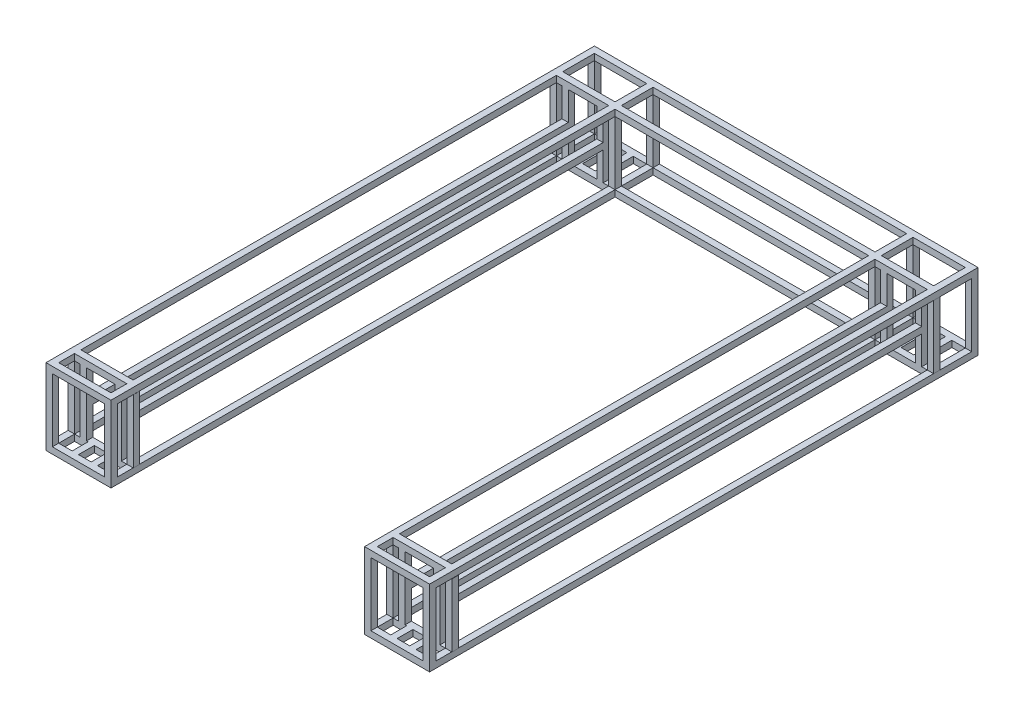
SolidWorks part; units mm, degrees
ref_plane "Front Plane" through (0, 0, 0) normal (0, 0, 1) x (1, 0, 0)
ref_plane "Top Plane" through (0, 0, 0) normal (0, 1, 0) x (1, 0, 0)
ref_plane "Right Plane" through (0, 0, 0) normal (1, 0, 0) x (0, 0, -1)
sketch "Sketch1" plane through (0, 0, 0) normal (0, 1, 0) x (1, 0, 0)
  line L0 (-400, 865) -> (-400, -865) construction
  line L1 (-400, 865) -> (400, 865) construction
  line L2 (-400, 865) -> (-400, -865) construction
  line L3 (-400, -865) -> (400, -865) construction
  line L4 (400, 865) -> (400, -865) construction
  line L5 (-400, 865) -> (400, -865) construction
  line L6 (-400, -865) -> (400, 865) construction
  line L7 (-400, 865) -> (-605, 865) construction
  line L8 (-400, -865) -> (-605, -865) construction
  line L9 (-605, 865) -> (-605, -865) construction
  line L10 (-605, 865) -> (-605, -865)
  line L11 (-605, 865) -> (-585, 865)
  line L12 (-605, -865) -> (-585, -865)
  line L13 (-585, 865) -> (-585, -865)
  line L14 (-400, 865) -> (-400, -865)
  line L15 (-400, 865) -> (-420, 865)
  line L16 (-400, -865) -> (-420, -865)
  line L17 (-420, 865) -> (-420, -865)
  line L18 (-420, -865) -> (-585, -865)
  line L21 (-420, -845) -> (-585, -845)
  line L22 (-585, -795) -> (-420, -795)
  line L25 (-585, -775) -> (-420, -775)
  line L26 (-585, 865) -> (-420, 865)
  line L29 (-585, 845) -> (-420, 845)
  line L30 (-420, 745) -> (-585, 745)
  line L33 (-420, 725) -> (-585, 725)
  line L34 (0, -55) -> (0, 55) construction
  line L35 (605, 865) -> (605, -865) construction
  line L36 (400, -865) -> (605, -865) construction
  line L37 (400, 865) -> (605, 865) construction
  line L38 (400, -865) -> (-400, 865) construction
  line L39 (400, 865) -> (-400, -865) construction
  line L40 (-400, 865) -> (-400, -865) construction
  line L41 (400, 865) -> (400, -865) construction
  line L42 (400, 865) -> (400, -865) construction
  line L43 (420, 725) -> (585, 725)
  line L46 (420, 745) -> (585, 745)
  line L47 (585, 845) -> (420, 845)
  line L50 (585, 865) -> (420, 865)
  line L51 (585, -775) -> (420, -775)
  line L54 (585, -795) -> (420, -795)
  line L55 (420, -845) -> (585, -845)
  line L58 (420, -865) -> (585, -865)
  line L59 (420, 865) -> (420, -865)
  line L60 (400, -865) -> (420, -865)
  line L61 (400, 865) -> (420, 865)
  line L62 (400, 865) -> (400, -865)
  line L63 (585, 865) -> (585, -865)
  line L64 (605, -865) -> (585, -865)
  line L65 (605, 865) -> (585, 865)
  line L66 (605, 865) -> (605, -865)
  line L67 (-400, 865) -> (400, 865)
  line L68 (400, 845) -> (-400, 845)
  line L69 (-400, 745) -> (400, 745)
  line L71 (400, 725) -> (-400, 725)
  point P0 (0, 0)
  dimension "D1" = 1730
  dimension "D2" = 800
  dimension "D3" = 165
  dimension "D4" = 20
  dimension "D5" = 20
  dimension "D6" = 20
  dimension "D7" = 20
  dimension "D8" = 100
  dimension "D9" = 20
  dimension "D10" = 20
  dimension "D11" = 50
extrude "Boss-Extrude1" add sketch "Sketch1" along normal blind 20 contours L13 L11 L10 L12 | L15 L17 L16 L14 | L33 L17 L30 L13 | L13 L29 L17 L26 | L71 L62 L69 L14 | L68 L62 L67 L14 | L63 L50 L59 L47 | L61 L62 L60 L59 | L63 L46 L59 L43 | L66 L65 L63 L64 | L63 L51 L59 L54 | L63 L55 L59 L58 | L25 L13 L22 L17 | L17 L21 L13 L18
pattern_linear "LPattern1" count 2 spacing 220 along (0, -1, 0) of "Boss-Extrude1"
sketch "Sketch2" plane through (0, 0, 0) normal (0, 1, 0) x (1, 0, 0)
  line L0 (-585, 745) -> (-585, 725)
  line L1 (-605, 865) -> (-585, 865)
  line L2 (-605, 865) -> (-605, 845)
  line L3 (-605, 845) -> (-585, 845)
  line L4 (-585, 865) -> (-585, 845)
  line L5 (-585, 745) -> (-605.1132, 745)
  line L6 (-585, 725) -> (-605.1132, 725)
  line L7 (-605.1132, 745) -> (-605.1132, 725)
  line L8 (-420, 845) -> (-400, 845)
  line L9 (-420, 845) -> (-420, 865.7864)
  line L10 (-400, 845) -> (-400, 865.7864)
  line L11 (-420, 865.7864) -> (-400, 865.7864)
  line L12 (-585, -795) -> (-585, -775)
  line L13 (-400, 745) -> (-420, 745)
  line L14 (-400, 745) -> (-400, 725)
  line L15 (-400, 725) -> (-420, 725)
  line L16 (-420, 745) -> (-420, 725)
  line L17 (-585, -845) -> (-605, -845)
  line L18 (-585, -845) -> (-585, -865)
  line L19 (-585, -865) -> (-605, -865)
  line L20 (-605, -845) -> (-605, -865)
  line L21 (-420, -845) -> (-400, -845)
  line L22 (-420, -845) -> (-420, -865)
  line L23 (-420, -865) -> (-400, -865)
  line L24 (-400, -845) -> (-400, -865)
  line L25 (-585, -795) -> (-605.9457, -795)
  line L26 (-585, -775) -> (-605.9457, -775)
  line L27 (-605.9457, -795) -> (-605.9457, -775)
  line L28 (-420, -775) -> (-420, -795)
  line L29 (-420, -775) -> (-399.5604, -775)
  line L30 (-420, -795) -> (-399.5604, -795)
  line L31 (-399.5604, -775) -> (-399.5604, -795)
  line L32 (0, -55) -> (0, 55) construction
  line L33 (605.9457, -795) -> (605.9457, -775)
  line L34 (585, -775) -> (605.9457, -775)
  line L35 (585, -795) -> (605.9457, -795)
  line L36 (400, -845) -> (400, -865)
  line L37 (420, -865) -> (400, -865)
  line L38 (420, -845) -> (420, -865)
  line L39 (420, -845) -> (400, -845)
  line L40 (605, -845) -> (605, -865)
  line L41 (585, -865) -> (605, -865)
  line L42 (585, -845) -> (585, -865)
  line L43 (585, -845) -> (605, -845)
  line L44 (420, 745) -> (420, 725)
  line L45 (400, 725) -> (420, 725)
  line L46 (400, 745) -> (400, 725)
  line L47 (400, 745) -> (420, 745)
  line L48 (585, -795) -> (585, -775)
  line L49 (420, 865.7864) -> (400, 865.7864)
  line L50 (400, 845) -> (400, 865.7864)
  line L51 (420, 845) -> (420, 865.7864)
  line L52 (420, 845) -> (400, 845)
  line L53 (605.1132, 745) -> (605.1132, 725)
  line L54 (585, 725) -> (605.1132, 725)
  line L55 (585, 745) -> (605.1132, 745)
  line L56 (585, 865) -> (585, 845)
  line L57 (605, 845) -> (585, 845)
  line L58 (605, 865) -> (605, 845)
  line L59 (605, 865) -> (585, 865)
  line L60 (585, 745) -> (585, 725)
  line L61 (420, -795) -> (399.5604, -795)
  line L62 (399.5604, -775) -> (399.5604, -795)
  line L63 (420, -775) -> (399.5604, -775)
  line L64 (420, -775) -> (420, -795)
extrude "Boss-Extrude2" add sketch "Sketch2" against normal blind 200
sketch "Sketch3" plane through (0, -220, 0) normal (0, -1, 0) x (1, 0, 0)
  line L0 (-502.5, -845) -> (-502.5, 865) construction
  line L1 (-585, -845) -> (-420, -845) construction
  line L2 (-420, -745) -> (-585, -745) construction
  line L3 (-482.5, -745) -> (-462.5, -745)
  line L4 (-482.5, -745) -> (-482.5, -845)
  line L5 (-482.5, -845) -> (-462.5, -845)
  line L6 (-462.5, -745) -> (-462.5, -845)
  line L7 (-605, 865) -> (-400, 865) construction
  line L8 (-542.5, -745) -> (-522.5, -745)
  line L9 (-542.5, -745) -> (-542.5, -845)
  line L10 (-542.5, -845) -> (-522.5, -845)
  line L11 (-522.5, -745) -> (-522.5, -845)
  line L12 (-420, 845) -> (-585, 845) construction
  line L13 (-462.5, 845) -> (-482.5, 845)
  line L14 (-462.5, 845) -> (-462.5, 795)
  line L15 (-462.5, 795) -> (-482.5, 795)
  line L16 (-482.5, 845) -> (-482.5, 795)
  line L17 (-585, 795) -> (-420, 795) construction
  line L18 (0, -55) -> (0, 55) construction
  line L19 (-542.5, 845) -> (-522.5, 845)
  line L20 (-542.5, 845) -> (-542.5, 795)
  line L21 (-542.5, 795) -> (-522.5, 795)
  line L22 (-522.5, 845) -> (-522.5, 795)
  line L23 (522.5, 845) -> (522.5, 795)
  line L24 (542.5, 795) -> (522.5, 795)
  line L25 (542.5, 845) -> (542.5, 795)
  line L26 (542.5, 845) -> (522.5, 845)
  line L27 (482.5, 845) -> (482.5, 795)
  line L28 (462.5, 795) -> (482.5, 795)
  line L29 (462.5, 845) -> (462.5, 795)
  line L30 (462.5, 845) -> (482.5, 845)
  line L31 (522.5, -745) -> (522.5, -845)
  line L32 (542.5, -845) -> (522.5, -845)
  line L33 (542.5, -745) -> (542.5, -845)
  line L34 (542.5, -745) -> (522.5, -745)
  line L35 (462.5, -745) -> (462.5, -845)
  line L36 (482.5, -845) -> (462.5, -845)
  line L37 (482.5, -745) -> (482.5, -845)
  line L38 (482.5, -745) -> (462.5, -745)
  dimension "D1" = 20
  dimension "D2" = 20
  dimension "D3" = 20
  dimension "D4" = 20
  dimension "D5" = 20
  dimension "D6" = 20
  dimension "D7" = 20
  dimension "D8" = 20
extrude "Boss-Extrude3" add sketch "Sketch3" against normal blind 20
sketch "Sketch4" plane through (0, 0, -725) normal (0, 0, 1) x (1, 0, 0)
  line L0 (-502.5, 0) -> (-502.5, -200) construction
  line L1 (-585, 0) -> (-420, 0) construction
  line L2 (-585, -200) -> (-420, -200) construction
  line L3 (0, -55) -> (0, 55) construction
  line L4 (-437.5, 0) -> (-457.5, 0)
  line L5 (-437.5, 0) -> (-437.5, -200)
  line L6 (-437.5, -200) -> (-457.5, -200)
  line L7 (-457.5, 0) -> (-457.5, -200)
  line L8 (-547.5, 0) -> (-567.5, 0)
  line L9 (-547.5, 0) -> (-547.5, -200)
  line L10 (-547.5, -200) -> (-567.5, -200)
  line L11 (-567.5, 0) -> (-567.5, -200)
  line L12 (502.5, 0) -> (502.5, -200) construction
  line L13 (567.5, 0) -> (567.5, -200)
  line L14 (547.5, -200) -> (567.5, -200)
  line L15 (547.5, 0) -> (547.5, -200)
  line L16 (547.5, 0) -> (567.5, 0)
  line L17 (457.5, 0) -> (457.5, -200)
  line L18 (437.5, -200) -> (457.5, -200)
  line L19 (437.5, 0) -> (437.5, -200)
  line L20 (437.5, 0) -> (457.5, 0)
  dimension "D1" = 20
  dimension "D2" = 20
  dimension "D3" = 45
  dimension "D4" = 45
extrude "Boss-Extrude4" add sketch "Sketch4" against normal blind 20
pattern_linear "LPattern2" count 2 spacing 1520 along (0, 0, 1) of "Boss-Extrude4"
sketch "Sketch5" plane through (0, 0, -725) normal (0, 0, 1) x (1, 0, 0)
  line L0 (-547.5, -200) -> (-547.5, 0) construction
  line L5 (-547.5, 0) -> (-567.5, -200) construction
  line L6 (-567.5, 0) -> (-547.5, -200) construction
  line L7 (-585, -200) -> (-420, -200) construction
  line L8 (-502.5, 0) -> (-502.5, -200) construction
  line L9 (-585, 0) -> (-420, 0) construction
  line L10 (-567.5, -90) -> (-547.5, -90)
  line L11 (-567.5, -90) -> (-567.5, -110)
  line L12 (-567.5, -110) -> (-547.5, -110)
  line L13 (-547.5, -90) -> (-547.5, -110)
  line L14 (-567.5, -90) -> (-547.5, -110) construction
  line L15 (-567.5, -110) -> (-547.5, -90) construction
  line L16 (-437.5, -110) -> (-457.5, -90) construction
  line L17 (-437.5, -90) -> (-457.5, -110) construction
  line L18 (-457.5, -90) -> (-457.5, -110)
  line L19 (-437.5, -110) -> (-457.5, -110)
  line L20 (-437.5, -90) -> (-437.5, -110)
  line L21 (-437.5, -90) -> (-457.5, -90)
  line L22 (0, -132) -> (0, 132) construction
  line L23 (437.5, -90) -> (457.5, -110) construction
  line L24 (437.5, -110) -> (457.5, -90) construction
  line L25 (567.5, -110) -> (547.5, -90) construction
  line L26 (567.5, -90) -> (547.5, -110) construction
  line L27 (437.5, -90) -> (457.5, -90)
  line L28 (437.5, -90) -> (437.5, -110)
  line L29 (437.5, -110) -> (457.5, -110)
  line L30 (457.5, -90) -> (457.5, -110)
  line L31 (547.5, -90) -> (547.5, -110)
  line L32 (567.5, -110) -> (547.5, -110)
  line L33 (567.5, -90) -> (567.5, -110)
  line L34 (567.5, -90) -> (547.5, -90)
  point P0 (-557.5, -100)
  point P24 (-447.5, -100)
  point P35 (447.5, -100)
  point P36 (557.5, -100)
  dimension "D1" = 20
extrude "Boss-Extrude5" add sketch "Sketch5" along normal blind 1500
